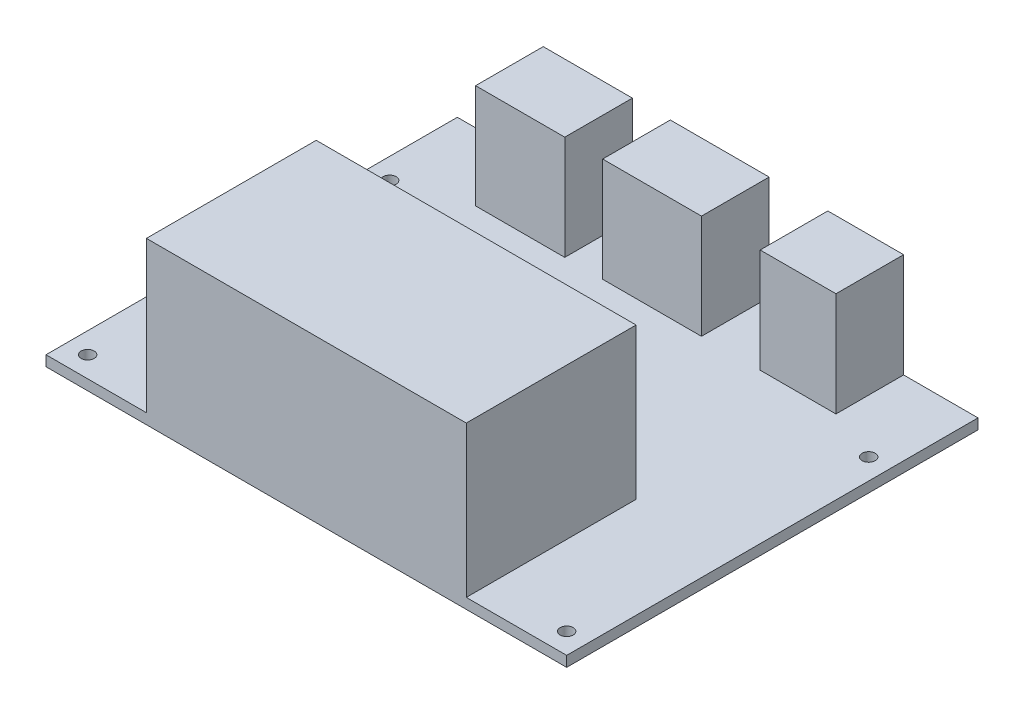
SolidWorks part; units mm, degrees
ref_plane "前视基准面" through (0, 0, 0) normal (0, 0, 1) x (1, 0, 0)
ref_plane "上视基准面" through (0, 0, 0) normal (0, 1, 0) x (1, 0, 0)
ref_plane "右视基准面" through (0, 0, 0) normal (1, 0, 0) x (0, 0, -1)
other "Configuration Table"
sketch "草图1" plane through (0, 0, 0) normal (0, 1, 0) x (1, 0, 0)
  line L1 (-46, 22.5) -> (46, 22.5) construction
  line L2 (-46, 22.5) -> (-46, -35.5) construction
  line L3 (-46, -35.5) -> (46, -35.5) construction
  line L4 (46, 22.5) -> (46, -35.5) construction
  line L5 (-50, -39.5) -> (50, -39.5)
  line L6 (-50, -39.5) -> (-50, 39.5)
  line L7 (-50, 39.5) -> (50, 39.5)
  line L8 (50, -39.5) -> (50, 39.5)
  line L9 (-50, -39.5) -> (50, 39.5) construction
  line L10 (-50, 39.5) -> (50, -39.5) construction
  circle A0 centre (-46, 22.5) radius 1.25
  circle A1 centre (46, 22.5) radius 1.25
  circle A2 centre (46, -35.5) radius 1.25
  circle A3 centre (-46, -35.5) radius 1.25
  point P8 (0, 0)
  point P15 (0, -35.5)
  dimension "D3" = 2.5
  dimension "D1" = 58
  dimension "D2" = 92
  dimension "D4" = 100
  dimension "D5" = 79
  dimension "D6" = 4
extrude "凸台-拉伸1" add sketch "草图1" along normal blind 2
sketch "草图2" plane through (0, 0, 0) normal (0, -1, 0) x (1, 0, 0)
  line L1 (-27.1122, 22.1061) -> (-4.4882, 22.1061)
  line L2 (-27.1122, 22.1061) -> (-27.1122, 8.129)
  line L3 (-27.1122, 8.129) -> (-4.4882, 8.129)
  line L4 (-4.4882, 22.1061) -> (-4.4882, 8.129)
extrude "凸台-拉伸2" add sketch "草图2" along normal blind 3
sketch "草图3" plane through (0, 2, 0) normal (0, 1, 0) x (1, 0, 0)
  line L0 (-50, -39.5) -> (50, -39.5) construction
  line L1 (-30.7186, -39.5) -> (30.7186, -39.5)
  line L2 (-30.7186, -39.5) -> (-30.7186, -6.8858)
  line L3 (-30.7186, -6.8858) -> (30.7186, -6.8858)
  line L4 (30.7186, -39.5) -> (30.7186, -6.8858)
  point P6 (0, -6.8858)
extrude "凸台-拉伸3" add sketch "草图3" along normal blind 29
sketch "草图4" plane through (0, 2, 0) normal (0, 1, 0) x (1, 0, 0)
  line L0 (50, 39.5) -> (-50, 39.5) construction
  line L1 (-33.5015, 39.5) -> (-16.3761, 39.5)
  line L2 (-33.5015, 39.5) -> (-33.5015, 26.5086)
  line L3 (-33.5015, 26.5086) -> (-16.3761, 26.5086)
  line L4 (-16.3761, 39.5) -> (-16.3761, 26.5086)
  line L6 (-9.0978, 39.5) -> (9.8828, 39.5)
  line L7 (-9.0978, 39.5) -> (-9.0978, 26.5086)
  line L8 (-9.0978, 26.5086) -> (9.8828, 26.5086)
  line L9 (9.8828, 39.5) -> (9.8828, 26.5086)
  line L10 (21.157, 39.5) -> (35.7135, 39.5)
  line L11 (21.157, 39.5) -> (21.157, 26.5086)
  line L12 (21.157, 26.5086) -> (35.7135, 26.5086)
  line L13 (35.7135, 39.5) -> (35.7135, 26.5086)
extrude "凸台-拉伸4" add sketch "草图4" along normal blind 20
